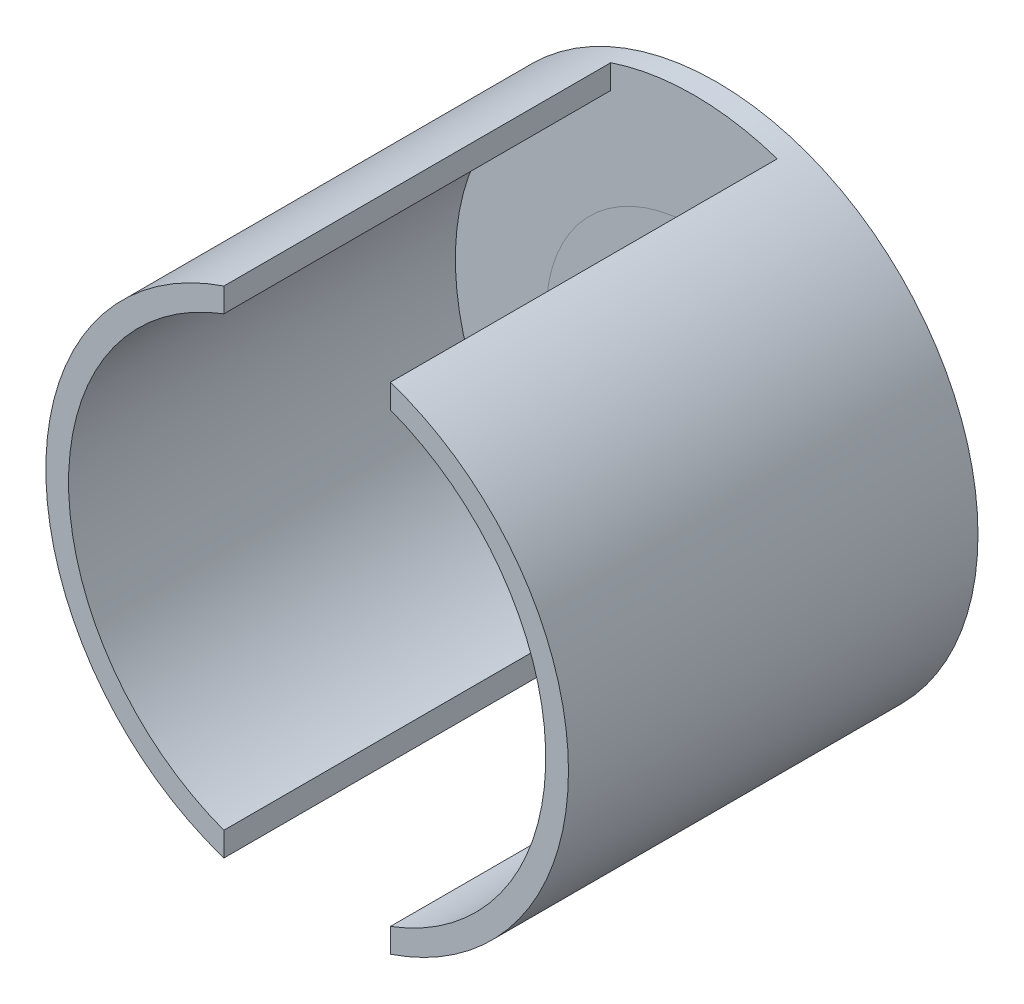
SolidWorks part; units mm, degrees
material "PET"
ref_plane "Piano frontale" through (0, 0, 0) normal (0, 0, 1) x (1, 0, 0)
ref_plane "Piano superiore" through (0, 0, 0) normal (0, 1, 0) x (1, 0, 0)
ref_plane "Piano destro" through (0, 0, 0) normal (1, 0, 0) x (0, 0, -1)
sketch "Schizzo1" plane through (0, 0, 0) normal (0, 0, 1) x (1, 0, 0)
  line L1 (5.5, 9) -> (-5.5, 9) construction
  line L2 (5.5, 9) -> (5.5, -9) construction
  line L3 (5.5, -9) -> (-5.5, -9) construction
  line L4 (-5.5, 9) -> (-5.5, -9) construction
  line L5 (5.5, 9) -> (-5.5, -9) construction
  line L6 (5.5, -9) -> (-5.5, 9) construction
  circle A0 centre (0, 0) radius 19.5
  circle A1 centre (5.5, 9) radius 1.75
  circle A2 centre (-5.5, 9) radius 1.75
  circle A3 centre (-5.5, -9) radius 1.75
  circle A4 centre (5.5, -9) radius 1.75
  dimension "D1" = 39
  dimension "D4" = 3.5
  dimension "D2" = 11
  dimension "D3" = 18
extrude "Estrusione-Estrusione1" add sketch "Schizzo1" along normal blind 3
sketch "Schizzo2" plane through (0, 0, 0) normal (0, 0, -1) x (-1, 0, 0)
  line L1 (7.6651, 5.25) -> (9.8301, 9)
  line L2 (9.8301, 9) -> (7.6651, 12.75)
  line L3 (7.6651, 12.75) -> (3.3349, 12.75)
  line L4 (3.3349, 12.75) -> (1.1699, 9)
  line L5 (1.1699, 9) -> (3.3349, 5.25)
  line L6 (3.3349, 5.25) -> (7.6651, 5.25)
  line L7 (3.3349, -12.75) -> (7.6651, -12.75)
  line L8 (7.6651, -12.75) -> (9.8301, -9)
  line L9 (9.8301, -9) -> (7.6651, -5.25)
  line L10 (7.6651, -5.25) -> (3.3349, -5.25)
  line L11 (3.3349, -5.25) -> (1.1699, -9)
  line L12 (1.1699, -9) -> (3.3349, -12.75)
  line L13 (-7.6651, -12.75) -> (-3.3349, -12.75)
  line L14 (-3.3349, -12.75) -> (-1.1699, -9)
  line L15 (-1.1699, -9) -> (-3.3349, -5.25)
  line L16 (-3.3349, -5.25) -> (-7.6651, -5.25)
  line L17 (-7.6651, -5.25) -> (-9.8301, -9)
  line L18 (-9.8301, -9) -> (-7.6651, -12.75)
  line L19 (-3.3349, 5.25) -> (-1.1699, 9)
  line L20 (-1.1699, 9) -> (-3.3349, 12.75)
  line L21 (-3.3349, 12.75) -> (-7.6651, 12.75)
  line L22 (-7.6651, 12.75) -> (-9.8301, 9)
  line L23 (-9.8301, 9) -> (-7.6651, 5.25)
  line L24 (-7.6651, 5.25) -> (-3.3349, 5.25)
  circle A0 centre (5.5, 9) radius 3.75 construction
  circle A1 centre (5.5, -9) radius 3.75 construction
  circle A2 centre (-5.5, -9) radius 3.75 construction
  circle A3 centre (-5.5, 9) radius 3.75 construction
  dimension "D1" = 7.5
extrude "Taglio-Estrusione1" cut sketch "Schizzo2" against normal blind 1
sketch "Schizzo5" plane through (0, 0, 3) normal (0, 0, 1) x (1, 0, 0)
  circle A0 centre (0, 0) radius 29.5085 construction
  circle A1 centre (0, 0) radius 34.72
  circle A2 centre (0, 0) radius 34.72
  circle A3 centre (0, 0) radius 29.5085
  circle A4 centre (0, 0) radius 34.52
  circle A5 centre (0, 0) radius 19.5
  circle A6 centre (0, 0) radius 19.5
  circle M5 centre (0, 0) radius 19.5
  dimension "D1" = 0
  dimension "D2" = 0
  dimension "D3" = 0.2
extrude "Estrusione-Estrusione4" add sketch "Schizzo5" against normal blind 3 separate body contours A4 A3 | A3 M5 | A2 | A6
sketch "Schizzo6" plane through (0, 0, 3) normal (0, 0, 1) x (1, 0, 0)
  circle A0 centre (0, 0) radius 31.52
  circle A1 centre (0, 0) radius 34.72
  circle A2 centre (0, 0) radius 34.72
  circle A5 centre (0, 0) radius 34.52 construction
  circle A6 centre (0, 0) radius 34.52
  dimension "D2" = 3
  dimension "D1" = 0
extrude "Estrusione-Estrusione5" add sketch "Schizzo6" along normal up to surface (51.1 mm away) contours A6 A0
sketch "Schizzo7" plane through (0, 0, 0) normal (0, 1, 0) x (1, 0, 0)
  line L0 (-31.72, -3) -> (31.72, -3) construction
  line L1 (-31.72, -3) -> (31.72, -3)
  line L3 (-11, -3) -> (11, -3)
  line L4 (-11, -3) -> (-11, -54.1)
  line L5 (-11, -54.1) -> (11, -54.1)
  line L6 (11, -3) -> (11, -54.1)
  line L10 (-31.52, -54.1) -> (31.52, -54.1) construction
  point P6 (0, -3)
  dimension "D1" = 22
extrude "Taglio-Estrusione2" cut sketch "Schizzo7" against normal through all both and the other way through all contours L6 L1 L4 L5
